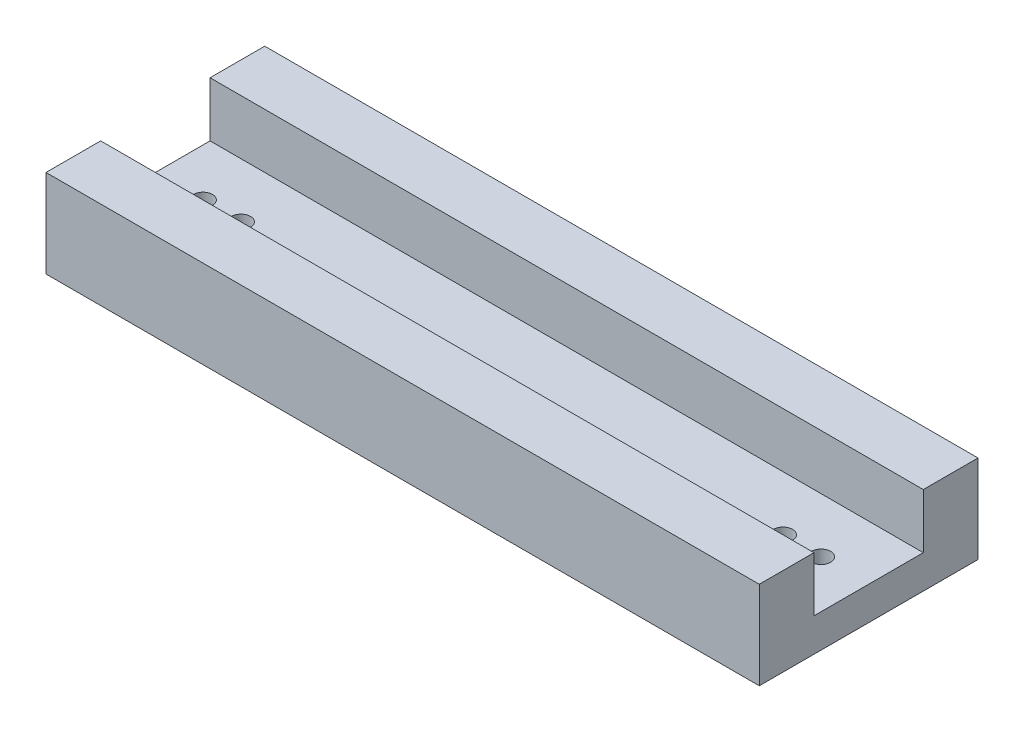
SolidWorks part; units mm, degrees
ref_plane "前视基准面" through (0, 0, 0) normal (0, 0, 1) x (1, 0, 0)
ref_plane "上视基准面" through (0, 0, 0) normal (0, 1, 0) x (1, 0, 0)
ref_plane "右视基准面" through (0, 0, 0) normal (1, 0, 0) x (0, 0, -1)
sketch "草图1" plane through (0, 0, 0) normal (1, 0, 0) x (0, 0, -1)
  line L0 (0, 18.5) -> (11.5, 18.5)
  line L1 (0, 0) -> (46, 0)
  line L2 (0, 0) -> (0, 18.5)
  line L3 (0, 18.5) -> (46, 18.5) construction
  line L4 (46, 0) -> (46, 18.5)
  line L5 (11.5, 18.5) -> (11.5, 7)
  line L6 (23, 18.5) -> (23, 0) construction
  line L7 (34.5, 18.5) -> (34.5, 7)
  line L8 (46, 18.5) -> (34.5, 18.5)
  line L9 (11.5, 7) -> (34.5, 7)
  dimension "D1" = 46
  dimension "D2" = 18.5
  dimension "D3" = 23
  dimension "D4" = 7
extrude "凸台-拉伸1" add sketch "草图1" along normal blind 150
sketch "草图2" plane through (0, 0, 0) normal (0, -1, 0) x (-1, 0, 0)
  line L0 (-150, 23) -> (-140, 23) construction
  line L1 (-150, 0) -> (-150, 46) construction
  line L2 (-75, 46) -> (-75, 0) construction
  line L3 (-150, 46) -> (0, 46) construction
  line L4 (-150, 0) -> (0, 0) construction
  circle A0 centre (-140, 23) radius 2
  circle A1 centre (-10, 23) radius 2
  circle A2 centre (-132, 23) radius 2
  circle A3 centre (-18, 23) radius 2
  dimension "D2" = 4
  dimension "D3" = 8
  dimension "D4" = 4
  dimension "D1" = 10
extrude "切除-拉伸1" cut sketch "草图2" against normal through all
